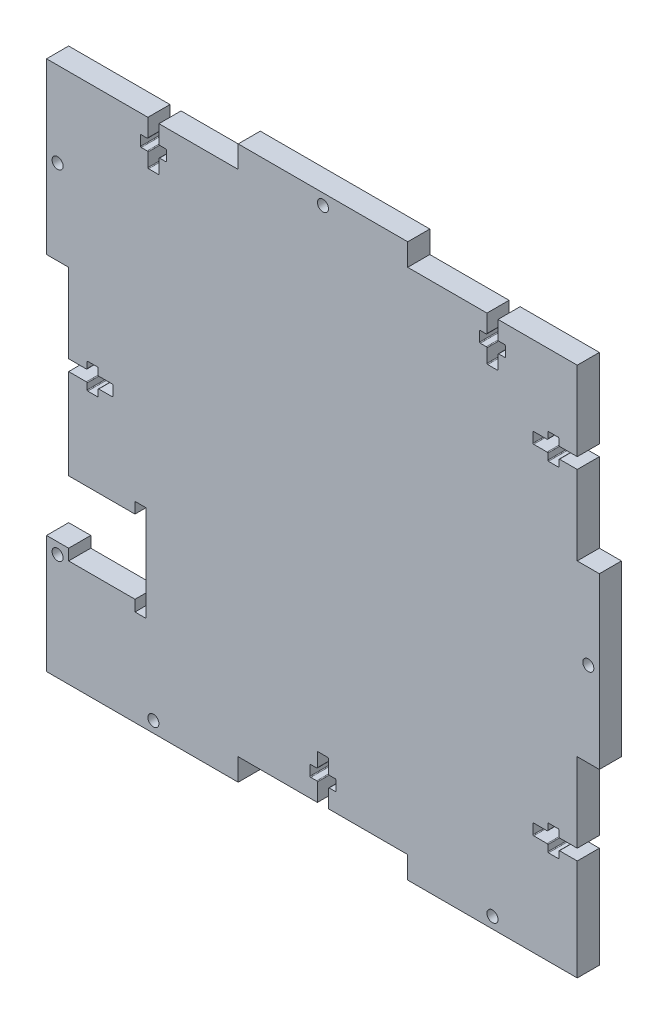
SolidWorks part; units mm, degrees
ref_plane "Front Plane" through (0, 0, 0) normal (0, 0, 1) x (1, 0, 0)
ref_plane "Top Plane" through (0, 0, 0) normal (0, 1, 0) x (1, 0, 0)
ref_plane "Right Plane" through (0, 0, 0) normal (1, 0, 0) x (0, 0, -1)
sketch "Sketch1" plane through (0, 0, 0) normal (0, 0, 1) x (1, 0, 0)
  line L0 (-69, 69) -> (-23, 69)
  line L5 (-75, -75) -> (75, -75) construction
  line L6 (-75, -75) -> (-75, 75) construction
  line L7 (-75, 75) -> (75, 75) construction
  line L8 (75, -75) -> (75, 75) construction
  line L9 (75, 23) -> (69, 23)
  line L10 (69, -23) -> (75, -23)
  line L11 (-69, -69) -> (69, -69) construction
  line L12 (-69, -69) -> (-69, 69) construction
  line L13 (-69, 69) -> (69, 69) construction
  line L14 (69, -69) -> (69, 69) construction
  line L15 (-69, -69) -> (69, 69) construction
  line L16 (69, -69) -> (69, -23)
  line L17 (-23, 69) -> (-23, 75)
  line L18 (-23, 75) -> (23, 75)
  line L19 (23, 75) -> (23, 69)
  line L20 (23, 69) -> (69, 69)
  line L21 (75, -23) -> (75, 23)
  line L22 (69, 23) -> (69, 69)
  line L23 (-75, 23) -> (-69, 23)
  line L24 (-69, 69) -> (-75, 69)
  line L25 (-75, 69) -> (-75, 23)
  line L26 (69, -69) -> (69, -75)
  line L27 (69, -75) -> (23, -75)
  line L28 (23, -75) -> (23, -69)
  line L29 (23, -69) -> (-23, -69)
  line L30 (-23, -69) -> (-23, -75)
  line L31 (-23, -75) -> (-69, -75)
  line L32 (-69, -75) -> (-69, -69) construction
  line L33 (-69, 23) -> (-69, -23)
  line L34 (-69, -23) -> (-75, -23)
  line L35 (-75, -23) -> (-75, -69)
  line L36 (-75, -69) -> (-69, -69) construction
  line L37 (-46, 69) -> (-46, -75) construction
  line L38 (-69, 69) -> (69, -69) construction
  line L39 (-75, -75) -> (-69, -75)
  line L40 (-75, -75) -> (-75, -69)
  point P0 (0, 0)
  point P6 (-7, -7)
  point P26 (0, -75)
  point P27 (-75, 0)
  dimension "D1" = 150
  dimension "D2" = 150
  dimension "D5" = 46
  dimension "D3" = 6
  dimension "D6" = 6
  dimension "D7" = 6
extrude "Box Side" add sketch "Sketch1" along normal blind 6
sketch "Sketch2" plane through (0, 0, 6) normal (0, 0, 1) x (1, 0, 0)
  line L0 (23, 72) -> (-23, 72) construction
  line L1 (23, 75) -> (23, 69) construction
  line L2 (-23, 69) -> (-23, 75) construction
  line L3 (-46, 69) -> (-46, -75) construction
  line L5 (0, 75) -> (0, 69) construction
  line L6 (-23, 75) -> (23, 75) construction
  line L7 (-69, 69) -> (69, 69) construction
  line L16 (-46, 69) -> (-46, -75) construction
  line L21 (0, -69) -> (0, 69) construction
  line L35 (-69, 69) -> (-23, 69) construction
  line L36 (-44.5, 69) -> (-44.5, 64.2)
  line L37 (-44.3, 64) -> (-42.7, 64)
  line L38 (-42.5, 63.8) -> (-42.5, 61.2)
  line L39 (-42.7, 61) -> (-44.3, 61)
  line L40 (-44.5, 60.8) -> (-44.5, 57.2)
  line L46 (-44.7, 57) -> (-47.3, 57)
  line L48 (-44.5, 69) -> (-47.5, 69)
  line L51 (-47.5, 60.8) -> (-47.5, 57.2)
  line L52 (-49.3, 61) -> (-47.7, 61)
  line L53 (-49.5, 63.8) -> (-49.5, 61.2)
  line L54 (-47.7, 64) -> (-49.3, 64)
  line L55 (-47.5, 69) -> (-47.5, 64.2)
  line L56 (47.5, 69) -> (47.5, 64.2)
  line L57 (47.7, 64) -> (49.3, 64)
  line L58 (49.5, 63.8) -> (49.5, 61.2)
  line L59 (49.3, 61) -> (47.7, 61)
  line L60 (47.5, 60.8) -> (47.5, 57.2)
  line L61 (44.5, 69) -> (47.5, 69)
  line L62 (44.7, 57) -> (47.3, 57)
  line L63 (44.5, 60.8) -> (44.5, 57.2)
  line L64 (42.7, 61) -> (44.3, 61)
  line L65 (42.5, 63.8) -> (42.5, 61.2)
  line L66 (44.3, 64) -> (42.7, 64)
  line L67 (44.5, 69) -> (44.5, 64.2)
  line L68 (-69, -69) -> (69, 69) construction
  line L69 (-69, -69) -> (69, 69) construction
  line L70 (75, 0) -> (69, 0) construction
  line L71 (72, 23) -> (72, -23) construction
  line L72 (69, 44.5) -> (64.2, 44.5)
  line L73 (64, 44.3) -> (64, 42.7)
  line L74 (63.8, 42.5) -> (61.2, 42.5)
  line L75 (61, 42.7) -> (61, 44.3)
  line L76 (60.8, 44.5) -> (57.2, 44.5)
  line L77 (57, 44.7) -> (57, 47.3)
  line L78 (69, 44.5) -> (69, 47.5)
  line L79 (60.8, 47.5) -> (57.2, 47.5)
  line L80 (61, 49.3) -> (61, 47.7)
  line L81 (63.8, 49.5) -> (61.2, 49.5)
  line L82 (64, 47.7) -> (64, 49.3)
  line L83 (69, 47.5) -> (64.2, 47.5)
  line L84 (69, -47.5) -> (64.2, -47.5)
  line L85 (64, -47.7) -> (64, -49.3)
  line L86 (63.8, -49.5) -> (61.2, -49.5)
  line L87 (61, -49.3) -> (61, -47.7)
  line L88 (60.8, -47.5) -> (57.2, -47.5)
  line L89 (69, -44.5) -> (69, -47.5)
  line L90 (57, -44.7) -> (57, -47.3)
  line L91 (60.8, -44.5) -> (57.2, -44.5)
  line L92 (61, -42.7) -> (61, -44.3)
  line L93 (63.8, -42.5) -> (61.2, -42.5)
  line L94 (64, -44.3) -> (64, -42.7)
  line L95 (69, -44.5) -> (64.2, -44.5)
  line L120 (-69, 69) -> (69, -69) construction
  line L121 (-69, 69) -> (69, -69) construction
  line L122 (-1.5, -69) -> (1.5, -69)
  line L123 (-23, -69) -> (23, -69) construction
  line L124 (1.5, -69) -> (1.5, -64.2)
  line L125 (1.7, -64) -> (3.3, -64)
  line L126 (3.5, -63.8) -> (3.5, -61.2)
  line L127 (3.3, -61) -> (1.7, -61)
  line L128 (1.5, -60.8) -> (1.5, -57.2)
  line L129 (1.3, -57) -> (-1.3, -57)
  line L130 (-1.5, -60.8) -> (-1.5, -57.2)
  line L131 (-3.3, -61) -> (-1.7, -61)
  line L132 (-3.5, -63.8) -> (-3.5, -61.2)
  line L133 (-1.7, -64) -> (-3.3, -64)
  line L134 (-1.5, -69) -> (-1.5, -64.2)
  line L135 (-69, -1.5) -> (-64.2, -1.5)
  line L136 (-64, -1.7) -> (-64, -3.3)
  line L137 (-63.8, -3.5) -> (-61.2, -3.5)
  line L138 (-61, -3.3) -> (-61, -1.7)
  line L139 (-60.8, -1.5) -> (-57.2, -1.5)
  line L140 (-57, 1.3) -> (-57, -1.3)
  line L141 (-60.8, 1.5) -> (-57.2, 1.5)
  line L142 (-61, 3.3) -> (-61, 1.7)
  line L143 (-63.8, 3.5) -> (-61.2, 3.5)
  line L144 (-64, 1.7) -> (-64, 3.3)
  line L145 (-69, 1.5) -> (-64.2, 1.5)
  line L146 (-69, -1.5) -> (-69, 1.5)
  line L147 (-69, -72) -> (-23, -72) construction
  line L148 (-23, 69) -> (-75, 69) construction
  line L149 (-23, -75) -> (-23, -69) construction
  line L150 (-69, -69) -> (-69, -75) construction
  line L151 (-75, -75) -> (-23, -75) construction
  circle A0 centre (0, 72) radius 1.5
  arc A1 (-44.5, 57.2) -> (-44.7, 57) centre (-44.7, 57.2) cw
  arc A2 (-44.3, 61) -> (-44.5, 60.8) centre (-44.3, 60.8) ccw
  arc A3 (-42.5, 61.2) -> (-42.7, 61) centre (-42.7, 61.2) cw
  arc A4 (-42.7, 64) -> (-42.5, 63.8) centre (-42.7, 63.8) cw
  arc A5 (-44.5, 64.2) -> (-44.3, 64) centre (-44.3, 64.2) ccw
  arc A6 (-47.5, 64.2) -> (-47.7, 64) centre (-47.7, 64.2) cw
  arc A7 (-49.3, 64) -> (-49.5, 63.8) centre (-49.3, 63.8) ccw
  arc A8 (-49.5, 61.2) -> (-49.3, 61) centre (-49.3, 61.2) ccw
  arc A9 (-47.7, 61) -> (-47.5, 60.8) centre (-47.7, 60.8) cw
  arc A10 (-47.5, 57.2) -> (-47.3, 57) centre (-47.3, 57.2) ccw
  arc A11 (47.5, 57.2) -> (47.3, 57) centre (47.3, 57.2) cw
  arc A12 (47.7, 61) -> (47.5, 60.8) centre (47.7, 60.8) ccw
  arc A13 (49.5, 61.2) -> (49.3, 61) centre (49.3, 61.2) cw
  arc A14 (49.3, 64) -> (49.5, 63.8) centre (49.3, 63.8) cw
  arc A15 (47.5, 64.2) -> (47.7, 64) centre (47.7, 64.2) ccw
  arc A16 (44.5, 64.2) -> (44.3, 64) centre (44.3, 64.2) cw
  arc A17 (42.7, 64) -> (42.5, 63.8) centre (42.7, 63.8) ccw
  arc A18 (42.5, 61.2) -> (42.7, 61) centre (42.7, 61.2) ccw
  arc A19 (44.3, 61) -> (44.5, 60.8) centre (44.3, 60.8) cw
  arc A20 (44.5, 57.2) -> (44.7, 57) centre (44.7, 57.2) ccw
  arc A21 (57.2, 44.5) -> (57, 44.7) centre (57.2, 44.7) cw
  arc A22 (61, 44.3) -> (60.8, 44.5) centre (60.8, 44.3) ccw
  arc A23 (61.2, 42.5) -> (61, 42.7) centre (61.2, 42.7) cw
  arc A24 (64, 42.7) -> (63.8, 42.5) centre (63.8, 42.7) cw
  arc A25 (64.2, 44.5) -> (64, 44.3) centre (64.2, 44.3) ccw
  arc A26 (64.2, 47.5) -> (64, 47.7) centre (64.2, 47.7) cw
  arc A27 (64, 49.3) -> (63.8, 49.5) centre (63.8, 49.3) ccw
  arc A28 (61.2, 49.5) -> (61, 49.3) centre (61.2, 49.3) ccw
  arc A29 (61, 47.7) -> (60.8, 47.5) centre (60.8, 47.7) cw
  arc A30 (57.2, 47.5) -> (57, 47.3) centre (57.2, 47.3) ccw
  arc A31 (57.2, -47.5) -> (57, -47.3) centre (57.2, -47.3) cw
  arc A32 (61, -47.7) -> (60.8, -47.5) centre (60.8, -47.7) ccw
  arc A33 (61.2, -49.5) -> (61, -49.3) centre (61.2, -49.3) cw
  arc A34 (64, -49.3) -> (63.8, -49.5) centre (63.8, -49.3) cw
  arc A35 (64.2, -47.5) -> (64, -47.7) centre (64.2, -47.7) ccw
  arc A36 (64.2, -44.5) -> (64, -44.3) centre (64.2, -44.3) cw
  arc A37 (64, -42.7) -> (63.8, -42.5) centre (63.8, -42.7) ccw
  arc A38 (61.2, -42.5) -> (61, -42.7) centre (61.2, -42.7) ccw
  arc A39 (61, -44.3) -> (60.8, -44.5) centre (60.8, -44.3) cw
  arc A40 (57.2, -44.5) -> (57, -44.7) centre (57.2, -44.7) ccw
  circle A41 centre (72, 0) radius 1.5
  arc A62 (1.5, -57.2) -> (1.3, -57) centre (1.3, -57.2) ccw
  arc A63 (1.7, -61) -> (1.5, -60.8) centre (1.7, -60.8) cw
  arc A64 (3.5, -61.2) -> (3.3, -61) centre (3.3, -61.2) ccw
  arc A65 (3.3, -64) -> (3.5, -63.8) centre (3.3, -63.8) ccw
  arc A66 (1.5, -64.2) -> (1.7, -64) centre (1.7, -64.2) cw
  arc A67 (-1.5, -64.2) -> (-1.7, -64) centre (-1.7, -64.2) ccw
  arc A68 (-3.3, -64) -> (-3.5, -63.8) centre (-3.3, -63.8) cw
  arc A69 (-3.5, -61.2) -> (-3.3, -61) centre (-3.3, -61.2) cw
  arc A70 (-1.7, -61) -> (-1.5, -60.8) centre (-1.7, -60.8) ccw
  arc A71 (-1.5, -57.2) -> (-1.3, -57) centre (-1.3, -57.2) cw
  arc A72 (-57.2, -1.5) -> (-57, -1.3) centre (-57.2, -1.3) ccw
  arc A73 (-61, -1.7) -> (-60.8, -1.5) centre (-60.8, -1.7) cw
  arc A74 (-61.2, -3.5) -> (-61, -3.3) centre (-61.2, -3.3) ccw
  arc A75 (-64, -3.3) -> (-63.8, -3.5) centre (-63.8, -3.3) ccw
  arc A76 (-64.2, -1.5) -> (-64, -1.7) centre (-64.2, -1.7) cw
  arc A77 (-64.2, 1.5) -> (-64, 1.7) centre (-64.2, 1.7) ccw
  arc A78 (-64, 3.3) -> (-63.8, 3.5) centre (-63.8, 3.3) cw
  arc A79 (-61.2, 3.5) -> (-61, 3.3) centre (-61.2, 3.3) cw
  arc A80 (-61, 1.7) -> (-60.8, 1.5) centre (-60.8, 1.7) ccw
  arc A81 (-57.2, 1.5) -> (-57, 1.3) centre (-57.2, 1.3) cw
  circle A82 centre (-46, -72) radius 1.5
  circle A83 centre (46, -72) radius 1.5
  circle A84 centre (-72, 46) radius 1.5
  circle A85 centre (-72, -46) radius 1.5
  point P6 (0, 72)
  point P38 (0, 0)
  point P56 (-46, 57)
  point P88 (46, 57)
  point P161 (57, 46)
  point P162 (57, -46)
  point P198 (0, -57)
  point P231 (-57, 0)
  point P234 (-42.5, 62.5)
  dimension "D1" = 3
  dimension "D2" = 0.2
  dimension "D8" = 0.2
  dimension "D14" = 3
  dimension "D4" = 3
  dimension "D7" = 1.5
  dimension "D10" = 3
  dimension "D12" = 1.5
  dimension "D9" = 12
  dimension "D11" = 5
  dimension "D13" = 7
  dimension "D3" = 12
  dimension "D5" = 7
  dimension "D6" = 5
extrude "Screw Cut-outs" cut sketch "Sketch2" against normal through all
sketch "Sketch3" plane through (0, 0, 6) normal (0, 0, 1) x (1, 0, 0)
  line L0 (-75, -75) -> (-23, -75) construction
  line L1 (-75, -49) -> (-48, -49)
  line L2 (-75, -49) -> (-75, -23)
  line L3 (-75, -23) -> (-48, -23)
  line L4 (-48, -49) -> (-48, -23)
  line L5 (-75, -23) -> (-75, -75) construction
  line L6 (-75, -46) -> (-48, -46)
  line L7 (-75, -26) -> (-48, -26)
  line L9 (-75, -26) -> (-69, -26)
  line L10 (-75, -26) -> (-75, -29)
  line L11 (-75, -29) -> (-69, -29)
  line L12 (-69, -26) -> (-69, -29)
  line L13 (-75, -46) -> (-69, -46)
  line L14 (-75, -46) -> (-75, -43)
  line L15 (-75, -43) -> (-69, -43)
  line L16 (-69, -46) -> (-69, -43)
  line L17 (-69, -26) -> (-75, -26)
  line L18 (-69, -26) -> (-69, -23)
  line L19 (-69, -23) -> (-75, -23)
  line L20 (-75, -26) -> (-75, -23)
  line L25 (-48, -23) -> (-51, -23)
  line L26 (-48, -23) -> (-48, -26)
  line L27 (-48, -26) -> (-51, -26)
  line L28 (-51, -23) -> (-51, -26)
  line L29 (-48, -46) -> (-51, -46)
  line L30 (-48, -46) -> (-48, -49)
  line L31 (-48, -49) -> (-51, -49)
  line L32 (-51, -46) -> (-51, -49)
  dimension "D1" = 26
  dimension "D2" = 27
  dimension "D3" = 26
  dimension "D4" = 20
  dimension "D5" = 3
  dimension "D6" = 3
  dimension "D7" = 6
  dimension "D8" = 3
  dimension "D9" = 3
extrude "Cut-Extrude1" cut sketch "Sketch3" against normal through all contours L7 L2 L6 L4
equation "\"filletRadius\"=0.2"
equation "\"D8@Sketch2\"=\"filletRadius\""
equation "\"D2@Sketch2\"=\"filletRadius\""
equation "\"fingerWidth\"= 46"
equation "\"D5@Sketch1\"=\"fingerWidth\""
equation "\"wallThickness\"= 6"
equation "\"D3@Sketch1\" = \"wallThickness\""
equation "\"D6@Sketch1\" = \"wallThickness\""
equation "\"D7@Sketch1\" = \"wallThickness\""
equation "\"D1@Box Side\" = \"wallThickness\""
equation "\"M3\"= 3"
equation "\"D14@Sketch2\"=\"M3\""
equation "\"D1@Sketch2\"=\"M3\""
equation "\"D12@Sketch2\"=\"M3\"/2"
equation "\"nutThickness\"=3"
equation "\"D10@Sketch2\" = \"nutThickness\""
equation "\"boltLength\"= 12"
equation "\"D9@Sketch2\" = \"boltLength\""
equation "\"distanceToNut\"= 5"
equation "\"D11@Sketch2\" = \"distanceToNut\""
equation "\"D13@Sketch2\" = \"nutWidth\""
equation "\"D7@Sketch2\"=\"M3\"/2"
equation "\"D4@Sketch2\" = \"nutThickness\""
equation "\"D3@Sketch2\" = \"boltLength\""
equation "\"D5@Sketch2\" = \"nutWidth\""
equation "\"D6@Sketch2\" = \"distanceToNut\""
equation "\"sideLength\"=150"
equation "\"D1@Sketch1\"=\"sideLength\""
equation "\"D2@Sketch1\"=\"sideLength\""
equation "\"nutWidth\"=7"
